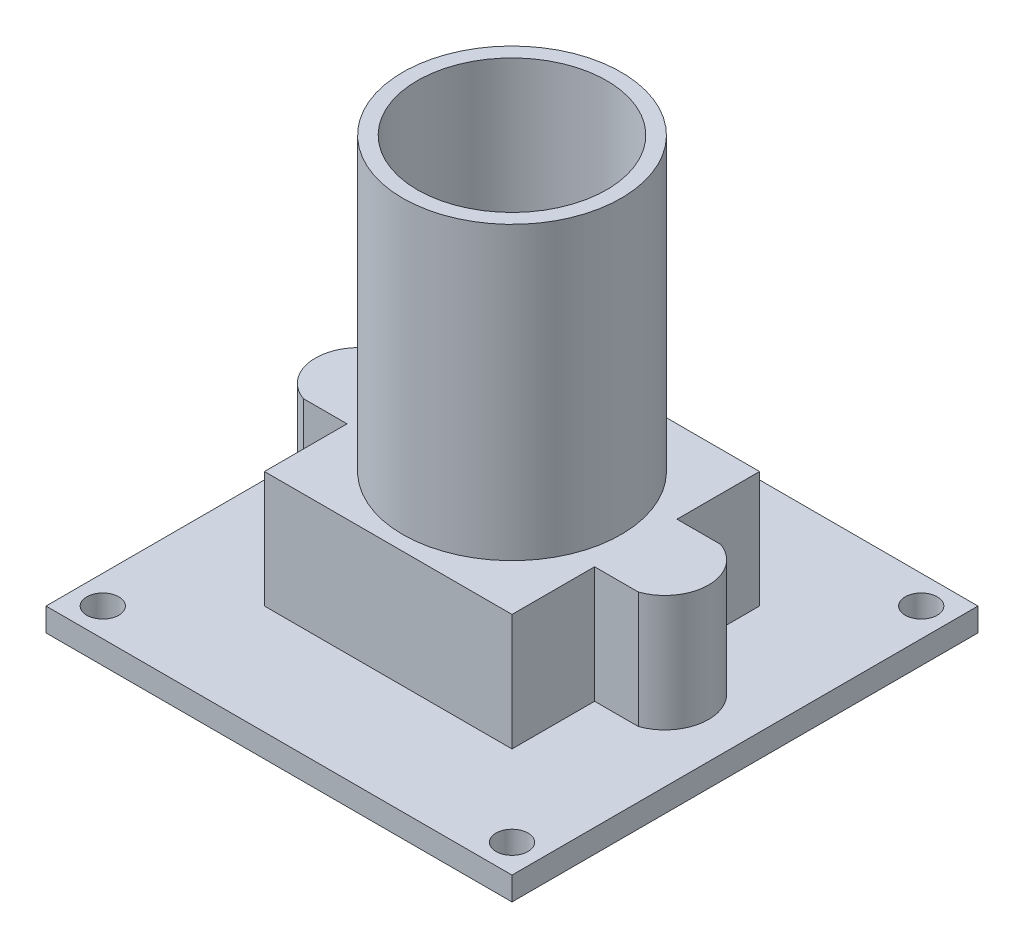
SolidWorks part; units mm, degrees
ref_plane "Front Plane" through (0, 0, 0) normal (0, 0, 1) x (1, 0, 0)
ref_plane "Top Plane" through (0, 0, 0) normal (0, 1, 0) x (1, 0, 0)
ref_plane "Right Plane" through (0, 0, 0) normal (1, 0, 0) x (0, 0, -1)
sketch "Sketch1" plane through (0, 0, 0) normal (0, 1, 0) x (1, 0, 0)
  line L0 (0, 0) -> (-32, 0)
  line L1 (-32, 0) -> (-32, 32)
  line L2 (-32, 32) -> (0, 32)
  line L3 (0, 32) -> (0, 0)
  dimension "D1" = 32
  dimension "D2" = 32
extrude "pcb_thickness" add sketch "Sketch1" along normal blind 1.6
sketch "Sketch2" plane through (0, 1.6, 0) normal (0, 1, 0) x (1, 0, 0)
  line L0 (-7.5, 24.5) -> (-24.5, 24.5)
  line L1 (-24.5, 24.5) -> (-24.5, 7.5)
  line L2 (-24.5, 7.5) -> (-7.5, 7.5)
  line L3 (-7.5, 7.5) -> (-7.5, 24.5)
  line L4 (-7.5, 24.5) -> (-7.5, 32) construction
  line L5 (0, 32) -> (-32, 32) construction
  line L6 (-7.5, 24.5) -> (0, 24.5) construction
  line L7 (0, 0) -> (0, 32) construction
  line L8 (-24.5, 7.5) -> (-32, 7.5) construction
  line L9 (-32, 32) -> (-32, 0) construction
  line L10 (-24.5, 7.5) -> (-24.5, 0) construction
  line L11 (-32, 0) -> (0, 0) construction
  dimension "D1" = 17
extrude "lens_1" add sketch "Sketch2" along normal blind 8
sketch "Sketch3" plane through (0, 9.6, 0) normal (0, 1, 0) x (1, 0, 0)
  line L0 (-16, 16) -> (-16, 24.5) construction
  line L1 (-7.5, 24.5) -> (-24.5, 24.5) construction
  line L2 (-16, 16) -> (-24.5, 16) construction
  line L3 (-24.5, 24.5) -> (-24.5, 7.5) construction
  line L4 (-16, 16) -> (-16, 7.5) construction
  line L5 (-24.5, 7.5) -> (-7.5, 7.5) construction
  line L6 (-16, 16) -> (-7.5, 16) construction
  line L7 (-7.5, 7.5) -> (-7.5, 24.5) construction
  circle A0 centre (-16, 16) radius 7.5
  dimension "D1" = 15
extrude "lens_2" add sketch "Sketch3" along normal blind 20
sketch "Sketch6" plane through (0, 1.6, 0) normal (0, 1, 0) x (1, 0, 0)
  line L0 (-24.5, 18.8284) -> (-27.5, 18.8284)
  line L1 (-24.5, 24.5) -> (-24.5, 7.5) construction
  line L2 (-26.5, 16) -> (-26.5, 32) construction
  line L3 (-27.5, 13.1716) -> (-24.5, 13.1716)
  line L4 (-7.5, 18.8284) -> (-4.5, 18.8284)
  line L5 (-7.5, 7.5) -> (-7.5, 24.5) construction
  line L6 (0, 32) -> (-32, 32) construction
  line L7 (-4.5, 13.1716) -> (-7.5, 13.1716)
  line L8 (-7.5, 7.5) -> (-7.5, 24.5) construction
  line L9 (-26.5, 16) -> (-26.5, 0) construction
  line L10 (-32, 0) -> (0, 0) construction
  line L11 (-5.5, 16) -> (-5.5, 32) construction
  line L12 (-5.5, 16) -> (-5.5, 0) construction
  line L13 (-7.5, 13.1716) -> (-7.5, 18.8284)
  line L14 (-24.5, 13.1716) -> (-24.5, 18.8284)
  arc A0 (-27.5, 18.8284) -> (-27.5, 13.1716) centre (-26.5, 16) ccw
  arc A1 (-4.5, 18.8284) -> (-4.5, 13.1716) centre (-5.5, 16) cw
  dimension "D2" = 1
  dimension "D3" = 3
  dimension "D1" = 3
extrude "lens_3" add sketch "Sketch6" along normal blind 8
sketch "Sketch7" plane through (0, 29.6, 0) normal (0, 1, 0) x (1, 0, 0)
  circle A0 centre (-16, 16) radius 6.5
  circle A1 centre (-16, 16) radius 7.5 construction
  dimension "D1" = 13
extrude "lens_4" cut sketch "Sketch7" against normal blind 28
sketch "Sketch5" plane through (0, 1.6, 0) normal (0, 1, 0) x (1, 0, 0)
  line L0 (-32, 32) -> (0, 0) construction
  line L1 (-32, 0) -> (0, 32) construction
  circle A0 centre (-30.05, 30.05) radius 1.1
  circle A1 centre (-1.95, 30.05) radius 1.1
  circle A2 centre (-1.95, 1.95) radius 1.1
  circle A3 centre (-30.05, 1.95) radius 1.1
  dimension "D5" = 2.2
  dimension "D1" = 28.1
  dimension "D2" = 28.1
  dimension "D3" = 28.1
  dimension "D4" = 28.1
extrude "mounting_holes" cut sketch "Sketch5" against normal through all
